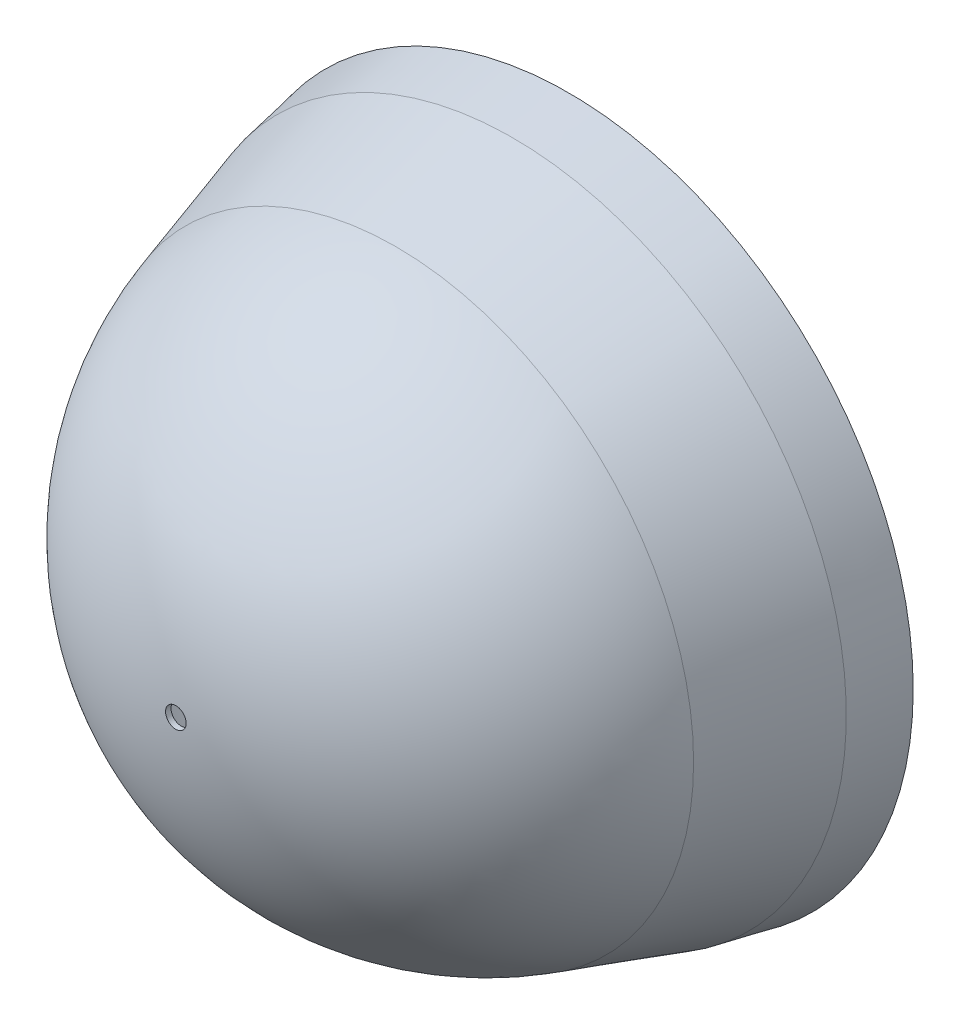
SolidWorks part; units mm, degrees
ref_plane "Front Plane" through (0, 0, 0) normal (0, 0, 1) x (1, 0, 0)
ref_plane "Top Plane" through (0, 0, 0) normal (0, 1, 0) x (1, 0, 0)
ref_plane "Right Plane" through (0, 0, 0) normal (1, 0, 0) x (0, 0, -1)
ref_axis "Axis1" through (0, 0, -134.3417) along (0, 0, 1)
sketch "Sketch1" plane through (0, 0, 0) normal (1, 0, 0) x (0, 0, -1)
  line L0 (-5.1816, 0) -> (-56.5616, 0) construction
  line L1 (50.2546, 67.9152) -> (77.3529, 76.2)
  line L2 (77.3529, 76.2) -> (90.0529, 78.6686)
  line L3 (579.0412, 139.1178) -> (604.4412, 140.0048) construction
  line L4 (579.0412, 0) -> (604.4412, 0) construction
  line L5 (90.0529, 78.6686) -> (103.7006, 81.3215)
  line L6 (108.839, 87.5548) -> (108.839, 114.3)
  line L7 (61.7034, 75.6285) -> (184.9302, 90.8062) construction
  arc A0 (50.2546, 67.9152) -> (0, 0) centre (71.0184, 0) ccw
  arc A1 (103.7006, 81.3215) -> (108.839, 87.5548) centre (102.489, 87.5548) ccw
  arc A3 (55.1007, 74.5189) -> (1.5478, -31.3094) centre (71.0184, 0) ccw construction
  arc A4 (55.1007, 74.5189) -> (579.0412, 139.1178) centre (684.1321, -2870.294) cw construction
  point P2 (262.3132, 0)
  dimension "D1" = 71.0184
  dimension "D2" = 152.4
  dimension "D7" = 3011.2462
  dimension "D19" = 6.35
  dimension "D3" = 77.3529
  dimension "D4" = 12.7
  dimension "D5" = 5.1816
  dimension "D6" = 149.0378
  dimension "D8" = 157.3373
  dimension "D9" = 267.4948
  dimension "D10" = 82.5345
  dimension "D11" = 17
  dimension "D12" = 2
  dimension "D13" = 280.0096
  dimension "D14" = 25.4
  dimension "D15" = 609.6228
  dimension "D16" = 11
  dimension "D17" = 152.4
  dimension "D18" = 108.839
  dimension "D20" = 228.6
  dimension "D21" = 151.257
  dimension "D22" = 7.022
  dimension "D23" = 1.3459
revolve "Revolve-Thin1" add sketch "Sketch1" angle 360 about axis through (0, 0, -134.3417) along (0, 0, 1) wall 2.54
sketch "Sketch5" plane through (0, 0, 0) normal (1, 0, 0) x (0, 0, -1)
  line L2 (-1.27, 0) -> (-23.8864, 0)
  line L3 (90.0529, 79.9624) -> (90.0529, 70.0009)
  line L4 (89.8106, 79.9153) -> (77.0452, 77.434)
  line L5 (77.0452, 77.434) -> (49.8833, 69.1297)
  line L6 (90.0529, 79.9624) -> (77.0452, 77.434)
  line L7 (77.0452, 77.434) -> (49.8833, 69.1297)
  line L8 (90.0529, 70.0009) -> (116.9003, 70.0009)
  line L9 (116.9003, 70.0009) -> (116.9003, 127.2178)
  line L10 (116.9003, 127.2178) -> (-23.8864, 127.2178)
  line L11 (-23.8864, 127.2178) -> (-23.8864, 0)
  arc A2 (49.8833, 69.1297) -> (-1.27, 0) centre (71.0184, 0) ccw
  arc A3 (49.8833, 69.1297) -> (-1.27, 0) centre (71.0184, 0) ccw
  dimension "D1" = 1.27
revolve "Cut-Revolve1" cut sketch "Sketch5" angle 360 about axis through (0, 0, -134.3417) along (0, 0, 1)
sketch "Sketch2" plane through (0, 0, 0) normal (1, 0, 0) x (0, 0, -1)
  line L0 (191.1932, 41.4345) -> (77.3529, 0)
  line L1 (77.3529, 0) -> (191.1932, -41.4345)
  line L2 (191.1932, -41.4345) -> (191.1932, 41.4345)
  point P2 (191.1932, 0)
  dimension "D1" = 40
extrude "Cut-Extrude1" [suppressed] cut sketch "Sketch2" along normal blind 101.6
pattern_circular "CirPattern1" [suppressed] count 8 over 360 about axis through (0, 0, -134.3417) along (0, 0, 1)
sketch "Sketch3" plane through (0, 0, 0) normal (0, 0, 1) x (1, 0, 0)
  circle A0 centre (0, 0) radius 2.3876
  dimension "D1" = 4.7752
extrude "Cut-Extrude2" [suppressed] cut sketch "Sketch3" against normal mid plane 25.4
sketch "Sketch6" [suppressed] plane through (0, 0, 0) normal (0, 1, 0) x (1, 0, 0)
  line L0 (-39.4204, -1.2579) -> (57.1257, -1.2579)
  line L1 (79.8287, 85.4323) -> (78.5327, 85.4323) construction
  point P2 (79.1807, 85.4323)
  dimension "D1" = 86.6902
sketch "Sketch7" plane through (0, 0, 0) normal (0, 0, 1) x (1, 0, 0)
  circle A0 centre (0, 0) radius 2.3876
  dimension "D1" = 4.7752
extrude "Cut-Extrude3" cut sketch "Sketch7" against normal mid plane 25.4
